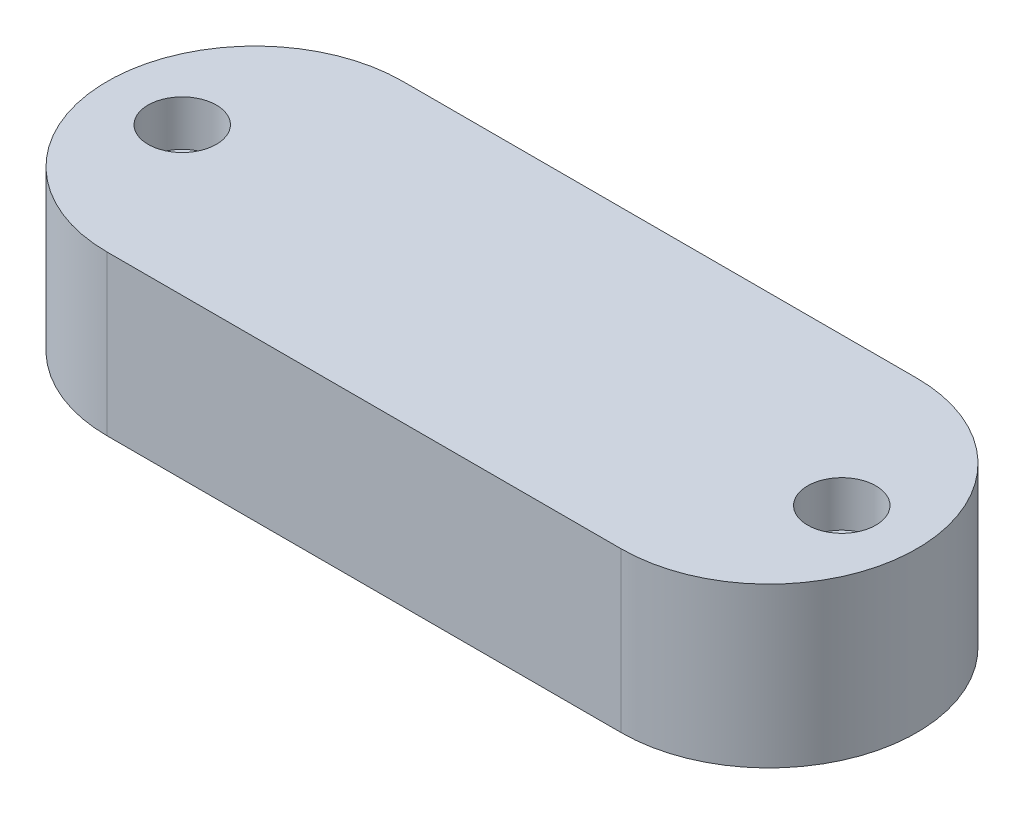
SolidWorks part; units mm, degrees
ref_plane "前视基准面" through (0, 0, 0) normal (0, 0, 1) x (1, 0, 0)
ref_plane "上视基准面" through (0, 0, 0) normal (0, 1, 0) x (1, 0, 0)
ref_plane "右视基准面" through (0, 0, 0) normal (1, 0, 0) x (0, 0, -1)
sketch "草图1" plane through (0, 0, 0) normal (0, 1, 0) x (1, 0, 0)
  line L0 (-11.3, 0) -> (11.3, 0) construction
  line L1 (-11.3, 6.5) -> (11.3, 6.5)
  line L2 (-11.3, -6.5) -> (11.3, -6.5)
  arc A0 (-11.3, 6.5) -> (-11.3, -6.5) centre (-11.3, 0) ccw
  arc A1 (11.3, -6.5) -> (11.3, 6.5) centre (11.3, 0) ccw
  point P2 (0, 0)
  point P8 (-17.8, 0)
  point P9 (17.8, 0)
  dimension "D1" = 6.5
  dimension "D2" = 22.6
  dimension "D3" = 35.6
extrude "凸台-拉伸1" add sketch "草图1" along normal blind 7
sketch "草图2" plane through (0, 7, 0) normal (0, 1, 0) x (1, 0, 0)
  line L0 (0, 0) -> (0, 4.4153) construction
  circle A0 centre (14.5, 0) radius 1.5
  circle A1 centre (-14.5, 0) radius 1.5
  dimension "D1" = 3
  dimension "D2" = 29
extrude "切除-拉伸1" cut sketch "草图2" against normal blind 2
